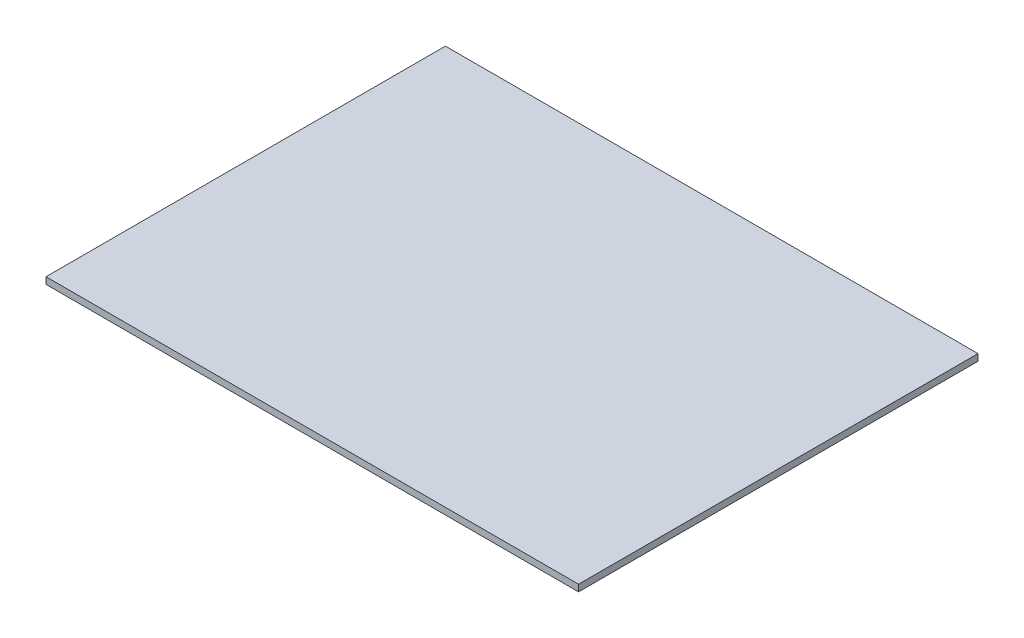
SolidWorks part; units mm, degrees
ref_plane "Front Plane" through (0, 0, 0) normal (0, 0, 1) x (1, 0, 0)
ref_plane "Top Plane" through (0, 0, 0) normal (0, 1, 0) x (1, 0, 0)
ref_plane "Right Plane" through (0, 0, 0) normal (1, 0, 0) x (0, 0, -1)
sketch "Sketch1" plane through (0, 0, 0) normal (0, 1, 0) x (1, 0, 0)
  line L1 (40, -30) -> (-40, -30)
  line L2 (40, -30) -> (40, 30)
  line L3 (40, 30) -> (-40, 30)
  line L4 (-40, -30) -> (-40, 30)
  line L5 (40, -30) -> (-40, 30) construction
  line L6 (40, 30) -> (-40, -30) construction
  point P0 (0, 0)
  dimension "D1" = 80
  dimension "D2" = 60
extrude "Boss-Extrude1" add sketch "Sketch1" against normal blind 1
